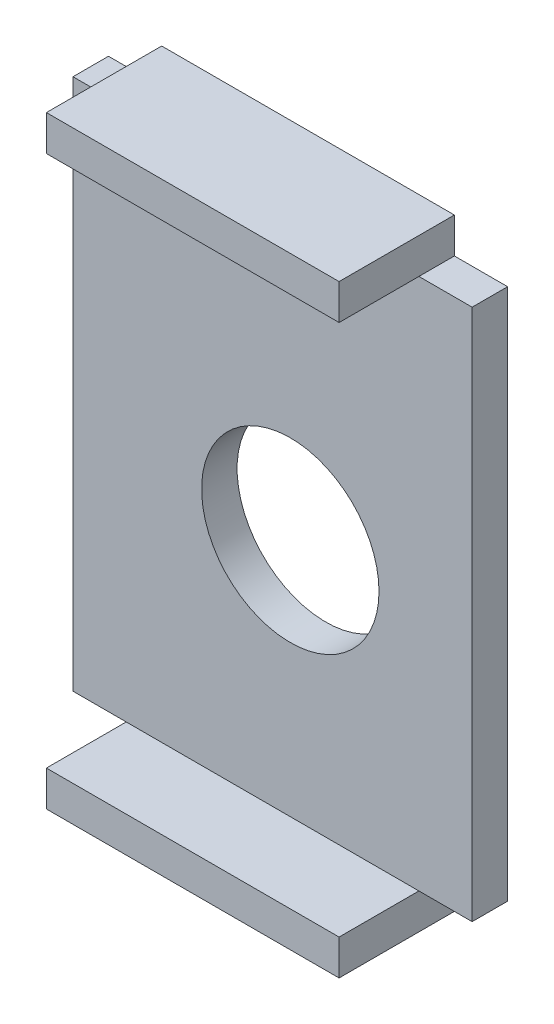
SolidWorks part; units mm, degrees
ref_plane "Front Plane" through (0, 0, 0) normal (0, 0, 1) x (1, 0, 0)
ref_plane "Top Plane" through (0, 0, 0) normal (0, 1, 0) x (1, 0, 0)
ref_plane "Right Plane" through (0, 0, 0) normal (1, 0, 0) x (0, 0, -1)
sketch "Sketch1" plane through (0, 0, 0) normal (0, 0, 1) x (1, 0, 0)
  line L5 (-22.5, -30) -> (22.5, -30)
  line L6 (-22.5, -30) -> (-22.5, 30)
  line L7 (-22.5, 30) -> (22.5, 30)
  line L8 (22.5, -30) -> (22.5, 30)
  line L9 (-22.5, -30) -> (22.5, 30) construction
  line L10 (-22.5, 30) -> (22.5, -30) construction
  circle A2 centre (2, -3) radius 10
  point P0 (0, 0)
  dimension "D3" = 20
  dimension "D1" = 60
  dimension "D2" = 45
  dimension "D4" = 20.5
  dimension "D5" = 3
extrude "Boss-Extrude1" add sketch "Sketch1" along normal mid plane 4
sketch "Sketch3" plane through (0, 0, -2) normal (0, 0, -1) x (-1, 0, 0)
  line L0 (-22.5, 30) -> (22.5, 30) construction
  line L1 (-16.5, 30) -> (16.5, 30)
  line L2 (-16.5, 30) -> (-16.5, 34)
  line L3 (-16.5, 34) -> (16.5, 34)
  line L4 (16.5, 30) -> (16.5, 34)
  line L5 (-22.5, -30) -> (-22.5, 30) construction
  line L6 (22.5, 30) -> (22.5, -30) construction
  line L7 (22.5, -30) -> (-22.5, -30) construction
  line L8 (-16.5, -30) -> (16.5, -30)
  line L9 (-16.5, -30) -> (-16.5, -34)
  line L10 (-16.5, -34) -> (16.5, -34)
  line L11 (16.5, -30) -> (16.5, -34)
  dimension "D1" = 6
  dimension "D2" = 6
  dimension "D3" = 4
extrude "Boss-Extrude3" add sketch "Sketch3" against normal blind 13
equation "\"padding\"=6"
equation "\"wall_thick_ness\"=4"
equation "\"D1@Sketch3\"=\"padding\""
equation "\"D2@Sketch3\"=\"padding\""
equation "\"D3@Sketch3\"=\"wall_thick_ness\""
equation "\"D1@Boss-Extrude1\"=\"wall_thick_ness\""
